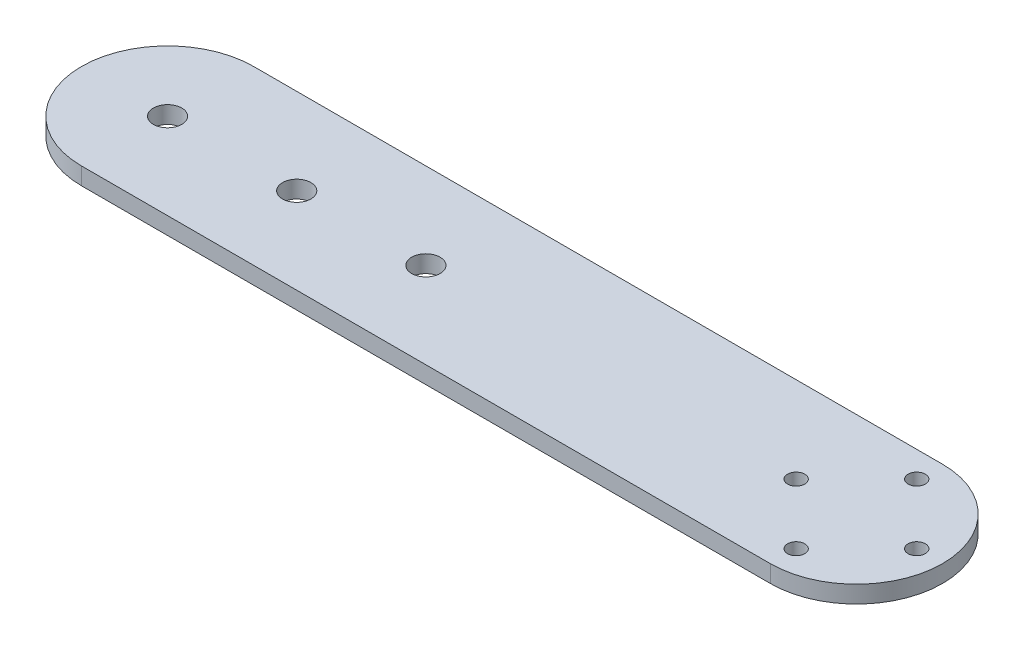
SolidWorks part; units mm, degrees
material "1060 Сплав"
ref_plane "Спереди" through (0, 0, 0) normal (0, 0, 1) x (1, 0, 0)
ref_plane "Сверху" through (0, 0, 0) normal (0, 1, 0) x (1, 0, 0)
ref_plane "Справа" through (0, 0, 0) normal (1, 0, 0) x (0, 0, -1)
sketch "Эскиз1" plane through (0, 0, 0) normal (0, 1, 0) x (1, 0, 0)
  line L0 (0, 10) -> (80, 10)
  line L1 (0, -10) -> (80, -10)
  arc A0 (0, 10) -> (0, -10) centre (0, 0) ccw
  circle A1 centre (30, 0) radius 1.65
  circle A2 centre (0, 0) radius 1.65
  circle A3 centre (15, 0) radius 1.65
  arc A6 (80, -10) -> (80, 10) centre (80, 0) ccw
  circle A7 centre (80, 0) radius 7 construction
  circle A8 centre (80, 7) radius 1
  circle A9 centre (87, 0) radius 1
  circle A10 centre (73, 0) radius 1
  circle A11 centre (80, -7) radius 1
  circle A12 centre (80, 0) radius 8 construction
  point P4 (15, 0)
  point P31 (80, 0)
  dimension "D1" = 65
  dimension "D2" = 30
  dimension "D3" = 20
  dimension "D4" = 14
  dimension "D5" = 16
  dimension "D7" = 3.3
  dimension "D6" = 80
extrude "Бобышка-Вытянуть1" add sketch "Эскиз1" along normal blind 2
